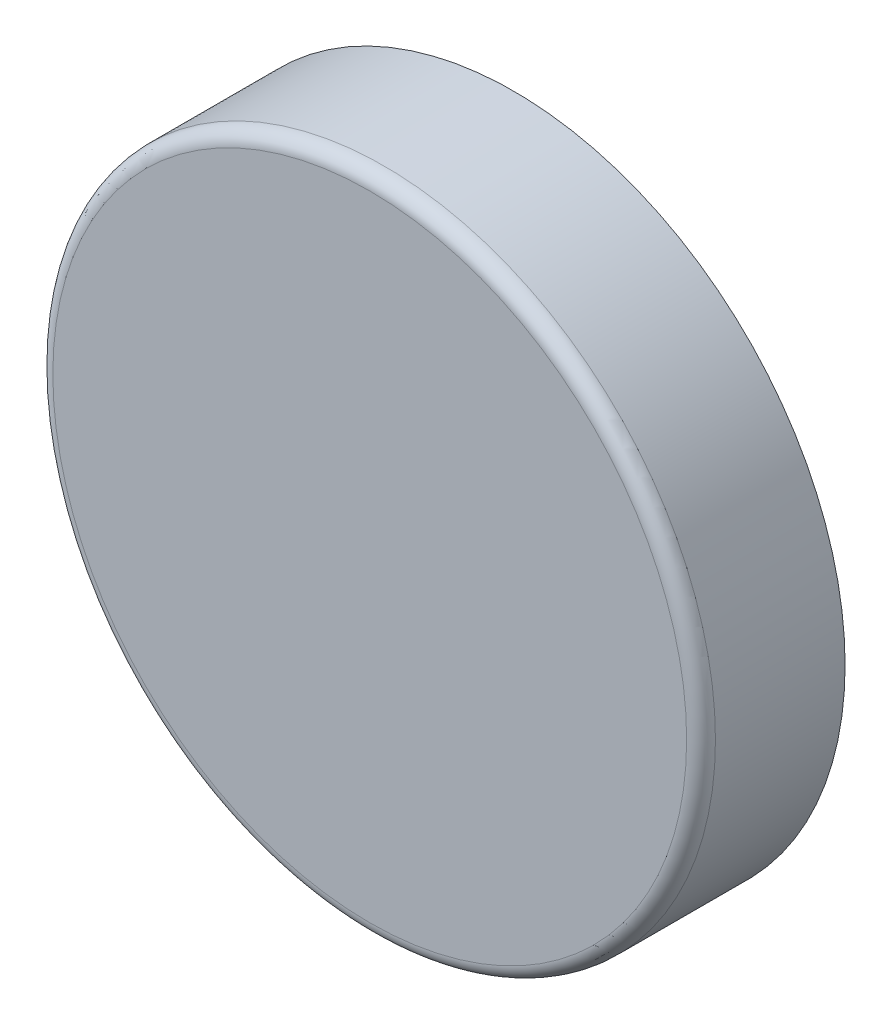
SolidWorks part; units mm, degrees
ref_plane "前视基准面" through (0, 0, 0) normal (0, 0, 1) x (1, 0, 0)
ref_plane "上视基准面" through (0, 0, 0) normal (0, 1, 0) x (1, 0, 0)
ref_plane "右视基准面" through (0, 0, 0) normal (1, 0, 0) x (0, 0, -1)
ref_plane "基准面1" through (0, 0, 0) normal (0, -1, 0) x (1, 0, 0)
sketch "草图1" plane through (0, 0, 0) normal (0, -1, 0) x (1, 0, 0)
  line L0 (1.65, 5) -> (-0.55, 5)
  line L1 (-0.55, 5) -> (-0.55, 4)
  line L2 (-0.55, 4) -> (1.75, 4)
  line L3 (1.75, 4) -> (1.75, 4.9)
  line L4 (-0.55, 5) -> (-0.55, 4) construction
  arc A0 (1.75, 4.9) -> (1.65, 5) centre (1.65, 4.9) ccw
  dimension "D3" = 0.1
  dimension "D1" = 2.3
  dimension "D2" = 1
revolve "旋转1" add sketch "草图1" angle 360 about L4
